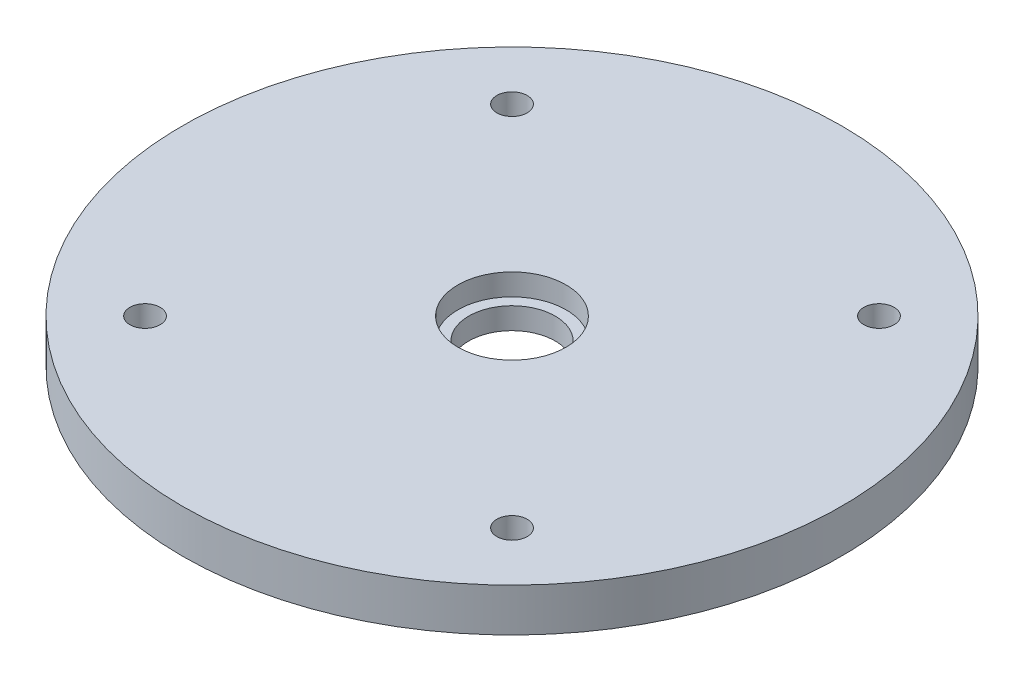
SolidWorks part; units mm, degrees
ref_plane "Front Plane" through (0, 0, 0) normal (0, 0, 1) x (1, 0, 0)
ref_plane "Top Plane" through (0, 0, 0) normal (0, 1, 0) x (1, 0, 0)
ref_plane "Right Plane" through (0, 0, 0) normal (1, 0, 0) x (0, 0, -1)
sketch "Sketch1" plane through (0, 0, 0) normal (0, 1, 0) x (1, 0, 0)
  circle A0 centre (0, 0) radius 38.1
  dimension "D1" = 76.2
extrude "Boss-Extrude1" add sketch "Sketch1" along normal blind 5
sketch "Sketch5" plane through (0, 5, 0) normal (0, 1, 0) x (1, 0, 0)
  line L0 (0, 0) -> (30, 0) construction
  line L1 (-21.2132, -21.2132) -> (21.2132, 21.2132) construction
  line L2 (21.2132, -21.2132) -> (-21.2132, 21.2132) construction
  circle A0 centre (0, 0) radius 30 construction
  circle A1 centre (21.2132, 21.2132) radius 1.75
  circle A2 centre (-21.2132, 21.2132) radius 1.75
  circle A3 centre (-21.2132, -21.2132) radius 1.75
  circle A4 centre (21.2132, -21.2132) radius 1.75
  dimension "D1" = 60
  dimension "D6" = 3.5
  dimension "D7" = 3.5
  dimension "D8" = 3.5
  dimension "D9" = 3.5
  dimension "D2" = 45
  dimension "D3" = 90
  dimension "D4" = 60
  dimension "D5" = 60
extrude "Cut-Extrude5" cut sketch "Sketch5" against normal blind 3
ref_plane "Plane1" through (0, 0, 0) normal (0, 1, 0) x (1, 0, 0)
sketch "Sketch6" plane through (0, 0, 0) normal (0, -1, 0) x (1, 0, 0)
  line L0 (0, 33.1) -> (0, -33.1) construction
  line L1 (33.1, 0) -> (-33.1, 0) construction
  circle A1 centre (0, -33.1) radius 2.5
  circle A2 centre (33.1, 0) radius 2.5
  circle A3 centre (0, 33.1) radius 2.5
  circle A4 centre (-33.1, 0) radius 2.5
  circle A5 centre (0, 0) radius 33.1 construction
  dimension "D1" = 5
  dimension "D2" = 66.2
  dimension "D3" = 33.1
  dimension "D4" = 66.2
  dimension "D5" = 66.2
extrude "Cut-Extrude6" cut sketch "Sketch6" against normal blind 3
sketch "Sketch7" plane through (0, 5, 0) normal (0, 1, 0) x (1, 0, 0)
  circle A0 centre (0, 0) radius 6.25
  dimension "D1" = 12.5
extrude "Cut-Extrude7" cut sketch "Sketch7" against normal blind 2.5
sketch "Sketch8" plane through (0, 5, 0) normal (0, 1, 0) x (1, 0, 0)
  circle A0 centre (0, 0) radius 5
  dimension "D1" = 10
extrude "Cut-Extrude10" cut sketch "Sketch8" against normal through all
